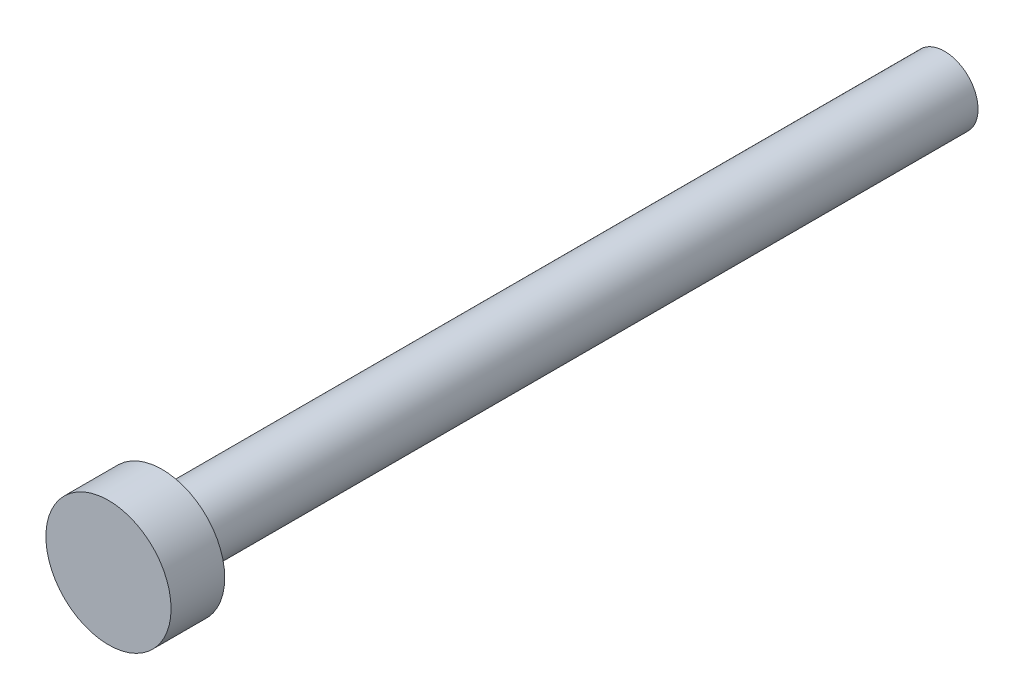
SolidWorks part; units mm, degrees
ref_plane "Plan de face" through (0, 0, 0) normal (0, 0, 1) x (1, 0, 0)
ref_plane "Plan de dessus" through (0, 0, 0) normal (0, 1, 0) x (1, 0, 0)
ref_plane "Plan de droite" through (0, 0, 0) normal (1, 0, 0) x (0, 0, -1)
sketch "Esquisse1" plane through (0, 0, 0) normal (0, 0, 1) x (1, 0, 0)
  circle A0 centre (0, 0) radius 2.8
  dimension "D1" = 5.6
extrude "Boss.-Extru.1" add sketch "Esquisse1" along normal blind 2.4
sketch "Esquisse2" plane through (0, 0, 0) normal (0, 0, -1) x (-1, 0, 0)
  circle A0 centre (0, 0) radius 1.5
  dimension "D1" = 3
extrude "Boss.-Extru.2" add sketch "Esquisse2" along normal blind 35
